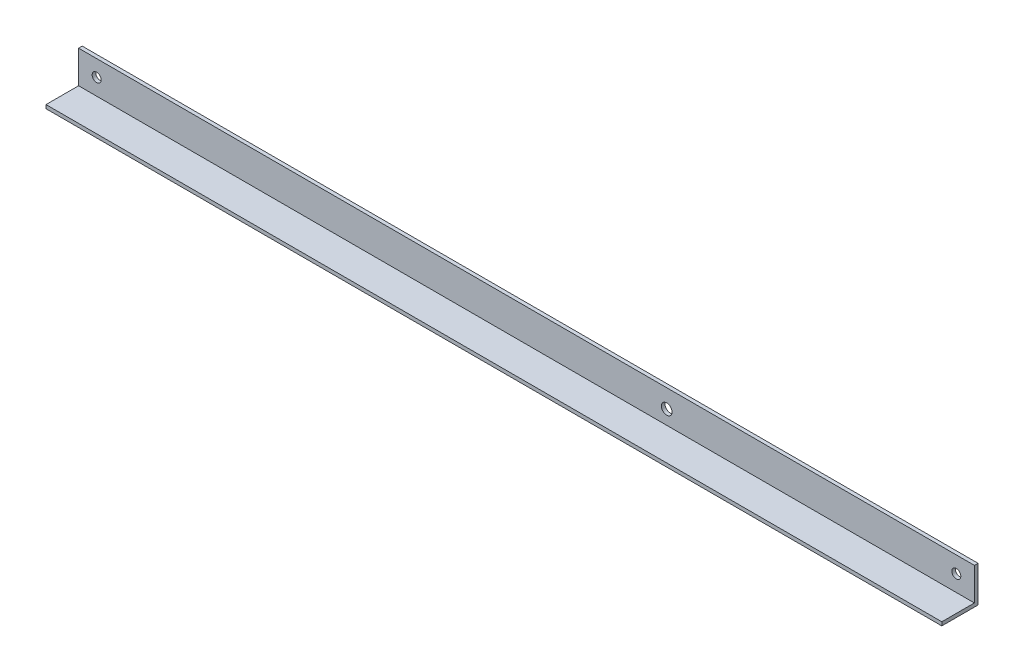
SolidWorks part; units mm, degrees
ref_plane "Front Plane" through (0, 0, 0) normal (0, 0, 1) x (1, 0, 0)
ref_plane "Top Plane" through (0, 0, 0) normal (0, 1, 0) x (1, 0, 0)
ref_plane "Right Plane" through (0, 0, 0) normal (1, 0, 0) x (0, 0, -1)
sketch "Sketch1" plane through (0, 0, 0) normal (1, 0, 0) x (0, 0, -1)
  line L0 (0, 20) -> (0, 0)
  line L1 (0, 0) -> (-20, 0)
  line L2 (-20, 0) -> (-20, 2)
  line L3 (-20, 2) -> (-2, 2)
  line L4 (-2, 2) -> (-2, 20)
  line L5 (-2, 20) -> (0, 20)
  dimension "D1" = 20
  dimension "D2" = 20
  dimension "D3" = 2
  dimension "D4" = 2
extrude "Boss-Extrude1" add sketch "Sketch1" along normal blind 170 and the other way blind 325
sketch "Sketch3" plane through (0, 0, 2) normal (0, 0, 1) x (1, 0, 0)
  line L0 (-325, 0) -> (170, 0) construction
  line L1 (-325, 20) -> (-325, 2) construction
  line L2 (-325, 20) -> (170, 20) construction
  line L3 (170, 20) -> (170, 2) construction
  circle A0 centre (0, 9.8) radius 2.95
  circle A1 centre (160, 11) radius 2.5
  circle A2 centre (-315, 11) radius 2.5
  dimension "D2" = 5.9
  dimension "D3" = 5
  dimension "D8" = 5
  dimension "D1" = 9.8
  dimension "D4" = 10
  dimension "D5" = 9
  dimension "D6" = 10
  dimension "D7" = 9
extrude "Cut-Extrude1" cut sketch "Sketch3" against normal blind 2
